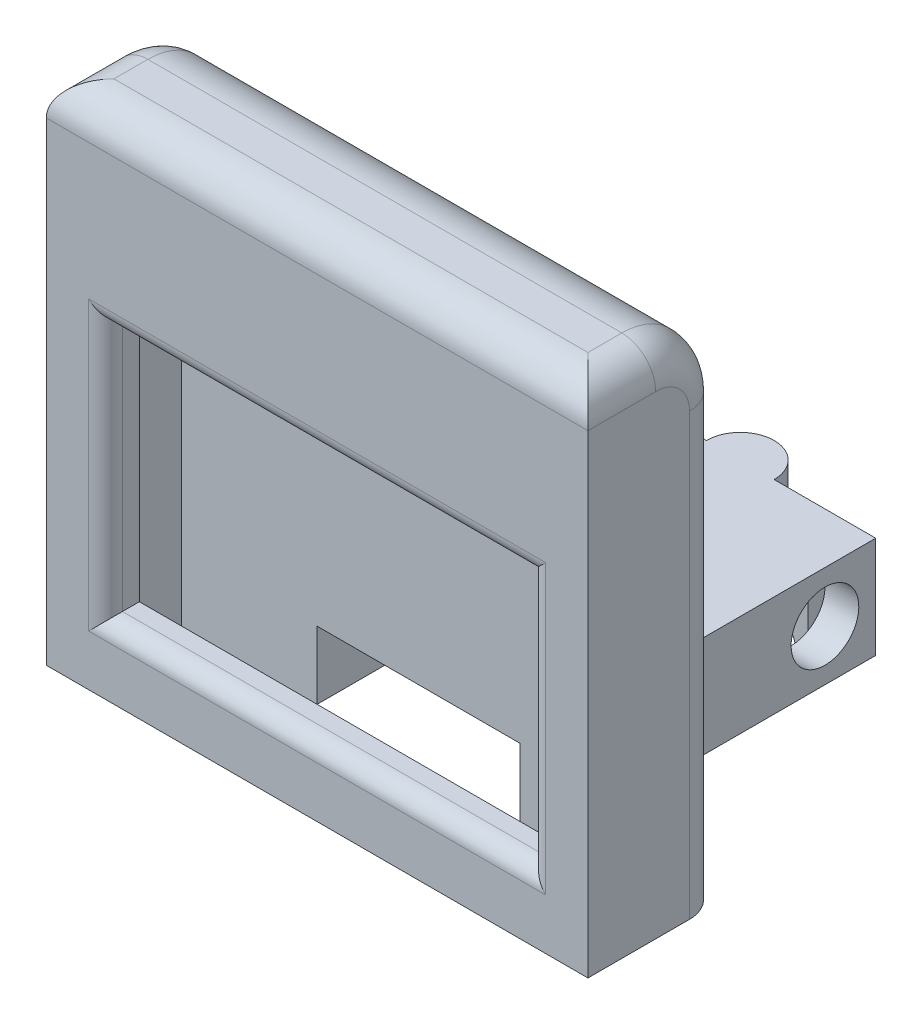
SolidWorks part; units mm, degrees
ref_plane "Plan de face" through (0, 0, 0) normal (0, 0, 1) x (1, 0, 0)
ref_plane "Plan de dessus" through (0, 0, 0) normal (0, 1, 0) x (1, 0, 0)
ref_plane "Plan de droite" through (0, 0, 0) normal (1, 0, 0) x (0, 0, -1)
sketch "Esquisse1" plane through (0, 0, 0) normal (0, 0, 1) x (1, 0, 0)
  line L1 (0, 0) -> (28, 0)
  line L2 (0, 0) -> (0, 28)
  line L3 (0, 28) -> (28, 28)
  line L4 (28, 0) -> (28, 28)
  dimension "D1" = 28
  dimension "D2" = 28
extrude "Boss.-Extru.1" add sketch "Esquisse1" along normal blind 4
shell "Coque1" thickness 2
sketch "Esquisse2" plane through (0, 0, 6) normal (0, 0, 1) x (1, 0, 0)
  line L0 (30, 30) -> (-2, 30) construction
  line L1 (1.5, 19) -> (26.5, 19)
  line L2 (1.5, 19) -> (1.5, 4)
  line L3 (1.5, 4) -> (26.5, 4)
  line L4 (26.5, 19) -> (26.5, 4)
  line L5 (-2, 0) -> (30, 0) construction
  point P4 (14, 19)
  point P7 (14, 30)
  dimension "D1" = 0
  dimension "D2" = 4
  dimension "D3" = 15
  dimension "D4" = 25
extrude "Enlèv. mat.-Extru.1" cut sketch "Esquisse2" against normal up to next
sketch "Esquisse8" plane through (0, 0, -2) normal (0, 0, -1) x (-1, 0, 0)
  line L0 (2, 0) -> (-30, 0) construction
  line L1 (-22, 6) -> (-6, 6)
  line L2 (-22, 6) -> (-22, 0)
  line L3 (-22, 0) -> (-6, 0)
  line L4 (-6, 6) -> (-6, 0)
  point P6 (-14, 6)
  point P7 (-14, 0)
  dimension "D1" = 0
  dimension "D2" = 16
  dimension "D3" = 6
extrude "Boss.-Extru.3" add sketch "Esquisse8" along normal blind 17
sketch "Esquisse10" plane through (0, 0, 0) normal (0, -1, 0) x (1, 0, 0)
  line L0 (22, -19) -> (22, -2) construction
  line L1 (8, -17) -> (20, -17)
  line L2 (8, -17) -> (8, 2.1533)
  line L3 (8, 2.1533) -> (20, 2.1533)
  line L4 (20, -17) -> (20, 2.1533)
  line L5 (6, -19) -> (6, -2) construction
  line L6 (22, -19) -> (6, -19) construction
  dimension "D1" = 2
  dimension "D2" = 2
  dimension "D3" = 2
extrude "Enlèv. mat.-Extru.3" cut sketch "Esquisse10" against normal blind 4
sketch "Esquisse11" plane through (22, 0, 0) normal (1, 0, 0) x (0, 0, -1)
  line L0 (19, 6) -> (19, 0) construction
  circle A0 centre (16, 3) radius 2
  point P4 (19, 3)
  dimension "D1" = 4
  dimension "D2" = 0
  dimension "D3" = 3
extrude "Enlèv. mat.-Extru.4" cut sketch "Esquisse11" against normal blind 2 contours A0
sketch "Esquisse13" plane through (6, 0, 0) normal (-1, 0, 0) x (0, 0, 1)
  line L0 (-19, 0) -> (-19, 6) construction
  circle A0 centre (-16, 3) radius 2
  point P4 (-19, 3)
  dimension "D1" = 4
  dimension "D2" = 3
  dimension "D3" = 0
extrude "Enlèv. mat.-Extru.9" cut sketch "Esquisse13" against normal blind 2
sketch "Esquisse15" plane through (0, 0, 0) normal (0, -1, 0) x (1, 0, 0)
  circle A0 centre (6, -2) radius 2
  dimension "D1" = 4
extrude "Boss.-Extru.5" add sketch "Esquisse15" against normal blind 6
sketch "Esquisse16" plane through (0, 0, 0) normal (0, -1, 0) x (1, 0, 0)
  circle A0 centre (22, -2) radius 2
  dimension "D1" = 4
extrude "Boss.-Extru.6" add sketch "Esquisse16" against normal blind 6
sketch "Esquisse17" plane through (0, 0, 0) normal (0, -1, 0) x (1, 0, 0)
  line L0 (8, -17) -> (20, -17) construction
  line L2 (8, -17) -> (20, -17) construction
  circle A0 centre (14, -19) radius 2
  point P4 (14, -17)
  point P6 (4.8543, 5.2069)
  dimension "D1" = 4
  dimension "D2" = 2
  dimension "D3" = 0
extrude "Boss.-Extru.7" add sketch "Esquisse17" against normal blind 6
sketch "Esquisse18" plane through (0, 0, 0) normal (0, -1, 0) x (1, 0, 0)
  circle A0 centre (6, -2) radius 1
  circle A1 centre (14, -19) radius 1
  circle A2 centre (22, -2) radius 1
  dimension "D1" = 2
  dimension "D2" = 2
  dimension "D3" = 2
extrude "Enlèv. mat.-Extru.10" cut sketch "Esquisse18" against normal blind 5.5
fillet "Congé1" radius 4 1 edges at (14, 30, -2)
fillet "Congé2" radius 2 7 edges at (30, 30, 4) (30, 28.8284, -0.8284) (-2, 30, 4) (-2, 28.8284, -0.8284) (14, 30, 6) (30, 13, -2) (-2, 13, -2)
fillet "Congé3" radius 1 4 edges at (26.5, 11.5, 6) (14, 19, 6) (1.5, 11.5, 6) (14, 4, 6)
sketch "Esquisse19" plane through (0, 0, -19) normal (0, 0, -1) x (-1, 0, 0)
  line L0 (-22, 0) -> (-16, 0) construction
  line L1 (-12, 6) -> (-16, 6) construction
  circle A0 centre (-18, 0) radius 1.25
  point P2 (0, 0)
  point P7 (-14, 6)
  dimension "D1" = 2.5
  dimension "D2" = 0
  dimension "D3" = 4
extrude "Enlèv. mat.-Extru.11" cut sketch "Esquisse19" against normal up to next
sketch "Esquisse20" plane through (0, 0, -2) normal (0, 0, -1) x (-1, 0, 0)
  text T0 "HUMANLAB"
  text T1 "PU1"
extrude "Enlèv. mat.-Extru.12" cut sketch "Esquisse20" against normal blind 1.5
